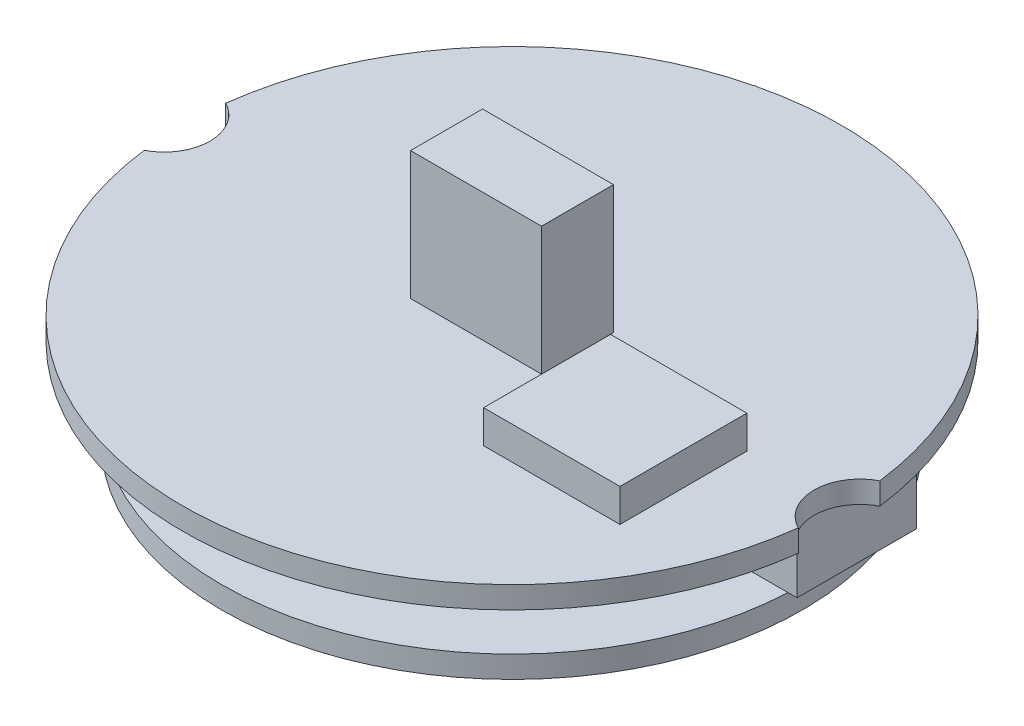
SolidWorks part; units mm, degrees
ref_plane "Front Plane" through (0, 0, 0) normal (0, 0, 1) x (1, 0, 0)
ref_plane "Top Plane" through (0, 0, 0) normal (0, 1, 0) x (1, 0, 0)
ref_plane "Right Plane" through (0, 0, 0) normal (1, 0, 0) x (0, 0, -1)
sketch "Sketch1" plane through (0, 0, 0) normal (0, 1, 0) x (1, 0, 0)
  circle A0 centre (0, 0) radius 7.9303
  dimension "D1" = 15.8605
extrude "Boss-Extrude1" add sketch "Sketch1" along normal blind 0.6
sketch "Sketch2" plane through (0, 0.6, 0) normal (0, 1, 0) x (1, 0, 0)
  line L1 (-8.1676, 2.8801) -> (8.1676, 2.8801)
  line L2 (-8.1676, 2.8801) -> (-8.1676, -0.384)
  line L3 (-8.1676, -0.384) -> (8.1676, -0.384)
  line L4 (8.1676, 2.8801) -> (8.1676, -0.384)
  line L5 (-8.1676, 2.8801) -> (8.1676, -0.384) construction
  line L6 (-8.1676, -0.384) -> (8.1676, 2.8801) construction
  point P0 (0, 1.248)
  point P5 (0, 1.248)
  point P6 (0, 0)
extrude "Boss-Extrude2" add sketch "Sketch2" along normal blind 1.8
sketch "Sketch3" plane through (0, 2.4, 0) normal (0, 1, 0) x (1, 0, 0)
  circle A0 centre (0, 0) radius 9
  circle A1 centre (-9.5, 0) radius 1.25
  circle A2 centre (9.5, 0) radius 1.25
  line M4 (8.1676, -0.384) -> (8.1676, 2.8801)
  line M5 (8.1676, 2.8801) -> (-8.1676, 2.8801)
  line M6 (-8.1676, 2.8801) -> (-8.1676, -0.384)
  line M7 (-8.1676, -0.384) -> (8.1676, -0.384)
  dimension "D1" = 18
  dimension "D4" = 2.5
  dimension "D2" = 9.5
  dimension "D3" = 9.5
extrude "Boss-Extrude3" add sketch "Sketch3" along normal blind 0.6 separate body contours A2 A0 A1 M4 M7 M6 M5 | M7 M4 M5 M6
sketch "Sketch4" plane through (0, 3, 0) normal (0, 1, 0) x (1, 0, 0)
  line L1 (2.6902, 0) -> (6.4152, 0)
  line L2 (2.6902, 0) -> (2.6902, -3.4663)
  line L3 (2.6902, -3.4663) -> (6.4152, -3.4663)
  line L4 (6.4152, 0) -> (6.4152, -3.4663)
extrude "Boss-Extrude4" add sketch "Sketch4" along normal blind 0.9
sketch "Sketch5" plane through (0, 3, 0) normal (0, 1, 0) x (1, 0, 0)
  line L1 (-1.7886, 0.983) -> (1.7886, 0.983)
  line L2 (-1.7886, 0.983) -> (-1.7886, -0.983)
  line L3 (-1.7886, -0.983) -> (1.7886, -0.983)
  line L4 (1.7886, 0.983) -> (1.7886, -0.983)
  line L5 (-1.7886, 0.983) -> (1.7886, -0.983) construction
  line L6 (-1.7886, -0.983) -> (1.7886, 0.983) construction
  point P0 (0, 0)
extrude "Boss-Extrude5" add sketch "Sketch5" along normal blind 3.5
